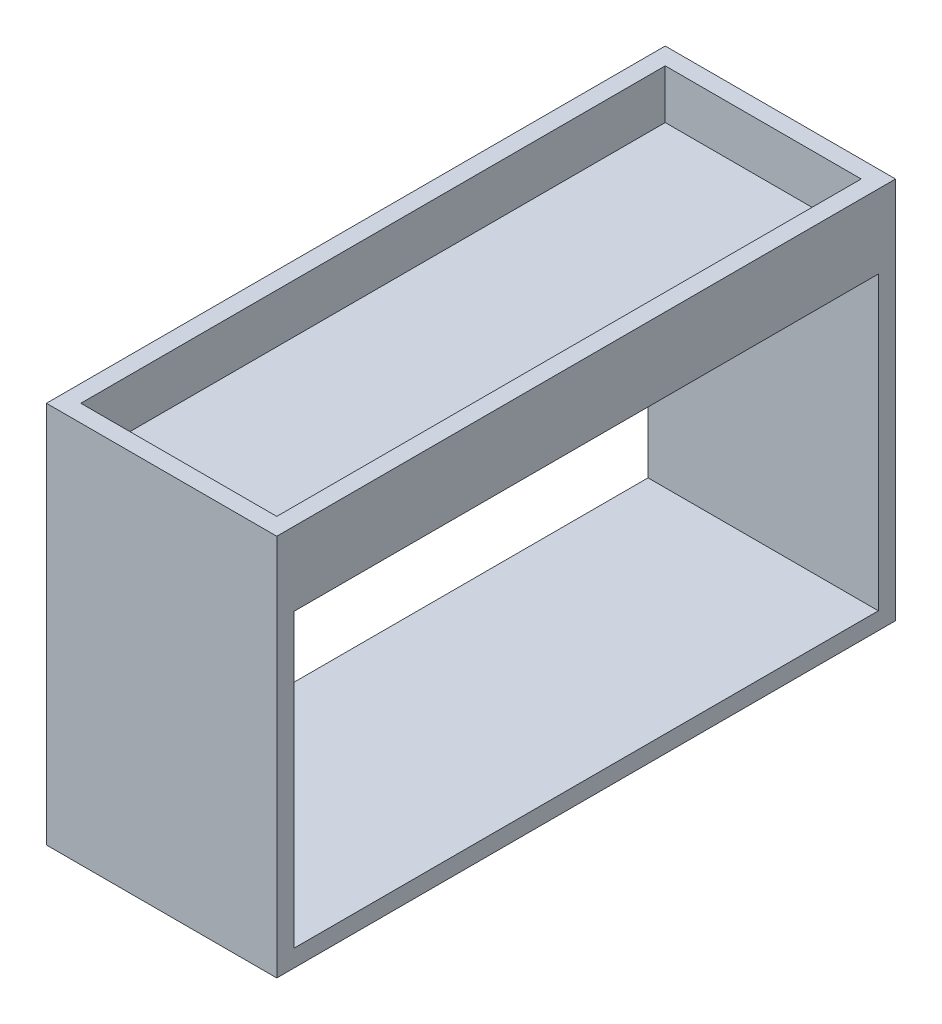
SolidWorks part; units mm, degrees
ref_plane "Front Plane" through (0, 0, 0) normal (0, 0, 1) x (1, 0, 0)
ref_plane "Top Plane" through (0, 0, 0) normal (0, 1, 0) x (1, 0, 0)
ref_plane "Right Plane" through (0, 0, 0) normal (1, 0, 0) x (0, 0, -1)
sketch "Sketch1" plane through (0, 0, 0) normal (0, 1, 0) x (1, 0, 0)
  line L1 (234.5, -630) -> (-234.5, -630)
  line L2 (234.5, -630) -> (234.5, 630)
  line L3 (234.5, 630) -> (-234.5, 630)
  line L4 (-234.5, -630) -> (-234.5, 630)
  line L5 (234.5, -630) -> (-234.5, 630) construction
  line L6 (234.5, 630) -> (-234.5, -630) construction
  point P0 (0, 0)
  dimension "D1" = 469
  dimension "D2" = 1260
extrude "Boss-Extrude1" add sketch "Sketch1" against normal blind 779
sketch "Sketch2" plane through (0, 0, 0) normal (0, 1, 0) x (1, 0, 0)
  line L0 (-234.5, 630) -> (-234.5, -630) construction
  line L1 (199.5, -595) -> (-199.5, -595)
  line L2 (199.5, -595) -> (199.5, 595)
  line L3 (199.5, 595) -> (-199.5, 595)
  line L4 (-199.5, -595) -> (-199.5, 595)
  line L5 (199.5, -595) -> (-199.5, 595) construction
  line L6 (199.5, 595) -> (-199.5, -595) construction
  line L7 (234.5, 630) -> (-234.5, 630) construction
  point P0 (0, 0)
  dimension "D1" = 35
  dimension "D2" = 35
extrude "Cut-Extrude1" cut sketch "Sketch2" against normal blind 100
sketch "Sketch3" plane through (-234.5, 0, 0) normal (-1, 0, 0) x (0, 0, 1)
  line L0 (-630, 0) -> (630, 0) construction
  line L1 (595, -744) -> (-595, -744)
  line L2 (595, -744) -> (595, -150)
  line L3 (595, -150) -> (-595, -150)
  line L4 (-595, -744) -> (-595, -150)
  line L5 (595, -744) -> (-595, -150) construction
  line L6 (595, -150) -> (-595, -744) construction
  line L7 (-630, -779) -> (-630, 0) construction
  line L8 (630, -779) -> (630, 0) construction
  line L9 (-630, -779) -> (630, -779) construction
  point P4 (0, -447)
  dimension "D1" = 150
  dimension "D2" = 35
  dimension "D3" = 35
  dimension "D4" = 35
extrude "Cut-Extrude3" cut sketch "Sketch3" against normal through all
